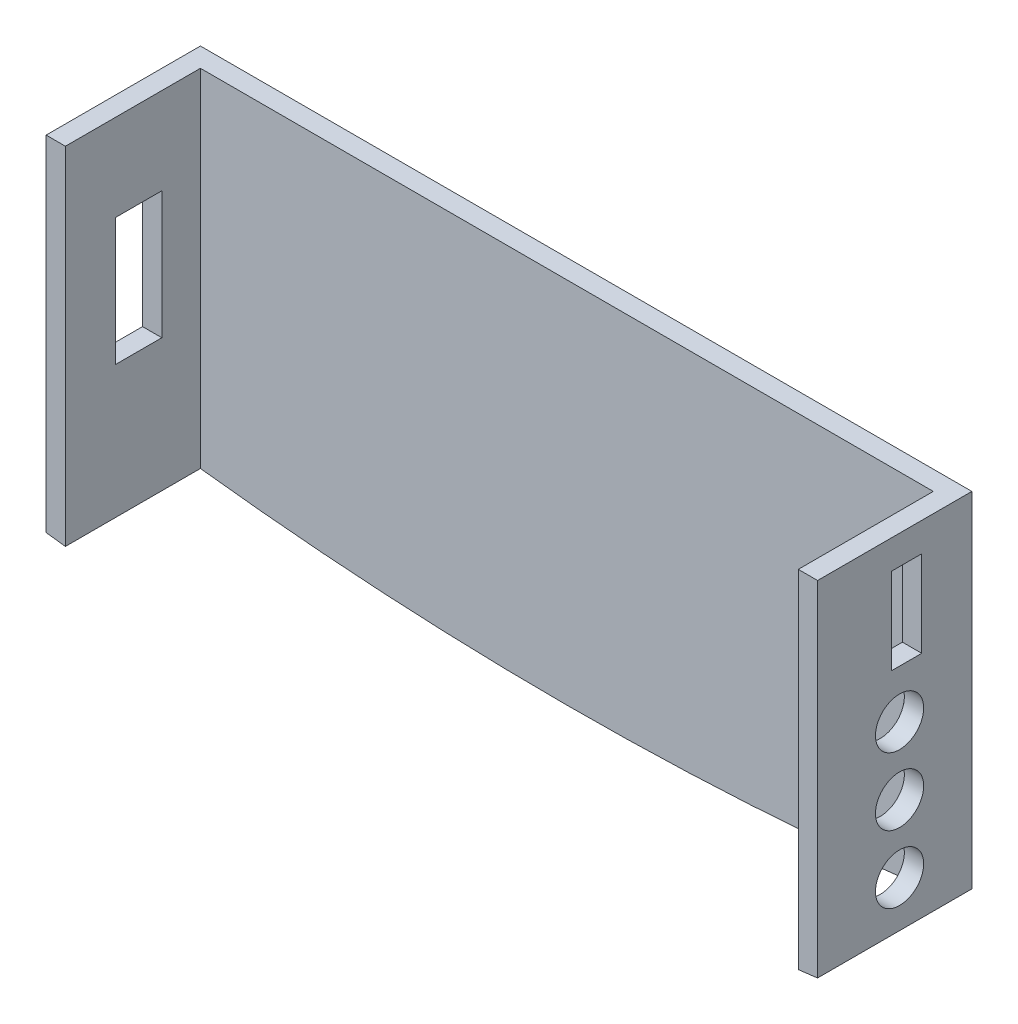
SolidWorks part; units mm, degrees
ref_plane "前视基准面" through (0, 0, 0) normal (0, 0, 1) x (1, 0, 0)
ref_plane "上视基准面" through (0, 0, 0) normal (0, 1, 0) x (1, 0, 0)
ref_plane "右视基准面" through (0, 0, 0) normal (1, 0, 0) x (0, 0, -1)
other "Configuration Table"
sketch "草图1" plane through (0, 0, 0) normal (0, 0, 1) x (1, 0, 0)
  line L1 (-10.4206, -29.3673) -> (-90.4206, -29.3673)
  line L2 (-10.4206, -29.3673) -> (-10.4206, 6.3327)
  line L3 (-10.4206, 6.3327) -> (-90.4206, 6.3327)
  line L4 (-90.4206, -29.3673) -> (-90.4206, 6.3327)
  line L5 (-10.4206, -29.3673) -> (-90.4206, 6.3327) construction
  line L6 (-10.4206, 6.3327) -> (-90.4206, -29.3673) construction
  arc A0 (-90.4206, -29.3673) -> (-10.4206, -29.3673) centre (-50.4206, 289.8866) ccw
  point P0 (-50.4206, -11.5173)
  dimension "D3" = 321.75
  dimension "D1" = 80
  dimension "D2" = 35.7
extrude "凸台-拉伸1" add sketch "草图1" along normal blind 16 contours L4 L1 L2 L3 | L1 A0
shell "抽壳1" thickness 2
sketch "草图2" plane through (-90.4206, 0, 0) normal (-1, 0, 0) x (0, 0, 1)
  line L6 (0, -29.3673) -> (0, 6.3327) construction
  line L7 (6, -2.6673) -> (10.8, -2.6673)
  line L8 (6, -2.6673) -> (6, -15.8673)
  line L9 (6, -15.8673) -> (10.8, -15.8673)
  line L10 (10.8, -2.6673) -> (10.8, -15.8673)
  line L11 (16, 6.3327) -> (0, 6.3327) construction
  dimension "D1" = 4.8
  dimension "D2" = 13.2
  dimension "D3" = 9
  dimension "D9" = 6
extrude "切除-拉伸3" cut sketch "草图2" against normal up to next
sketch "草图6" plane through (-10.4206, 0, 0) normal (1, 0, 0) x (0, 0, -1)
  line L1 (-8.36, 3.3327) -> (-5.2, 3.3327)
  line L2 (-8.36, 3.3327) -> (-8.36, -5.6073)
  line L3 (-8.36, -5.6073) -> (-5.2, -5.6073)
  line L4 (-5.2, 3.3327) -> (-5.2, -5.6073)
  line L8 (-16, 6.3327) -> (0, 6.3327) construction
  line L11 (0, -29.3673) -> (0, 6.3327) construction
  circle A0 centre (-7.5, -10.6073) radius 2.5
  circle A1 centre (-7.5, -17.6073) radius 2.5
  circle A2 centre (-7.5, -24.6073) radius 2.5
  dimension "D5" = 5
  dimension "D6" = 5
  dimension "D7" = 5
  dimension "D1" = 3.16
  dimension "D2" = 8.94
  dimension "D3" = 7.5
  dimension "D4" = 3
  dimension "D8" = 5
  dimension "D9" = 7
  dimension "D10" = 7
extrude "切除-拉伸4" cut sketch "草图6" against normal up to next
